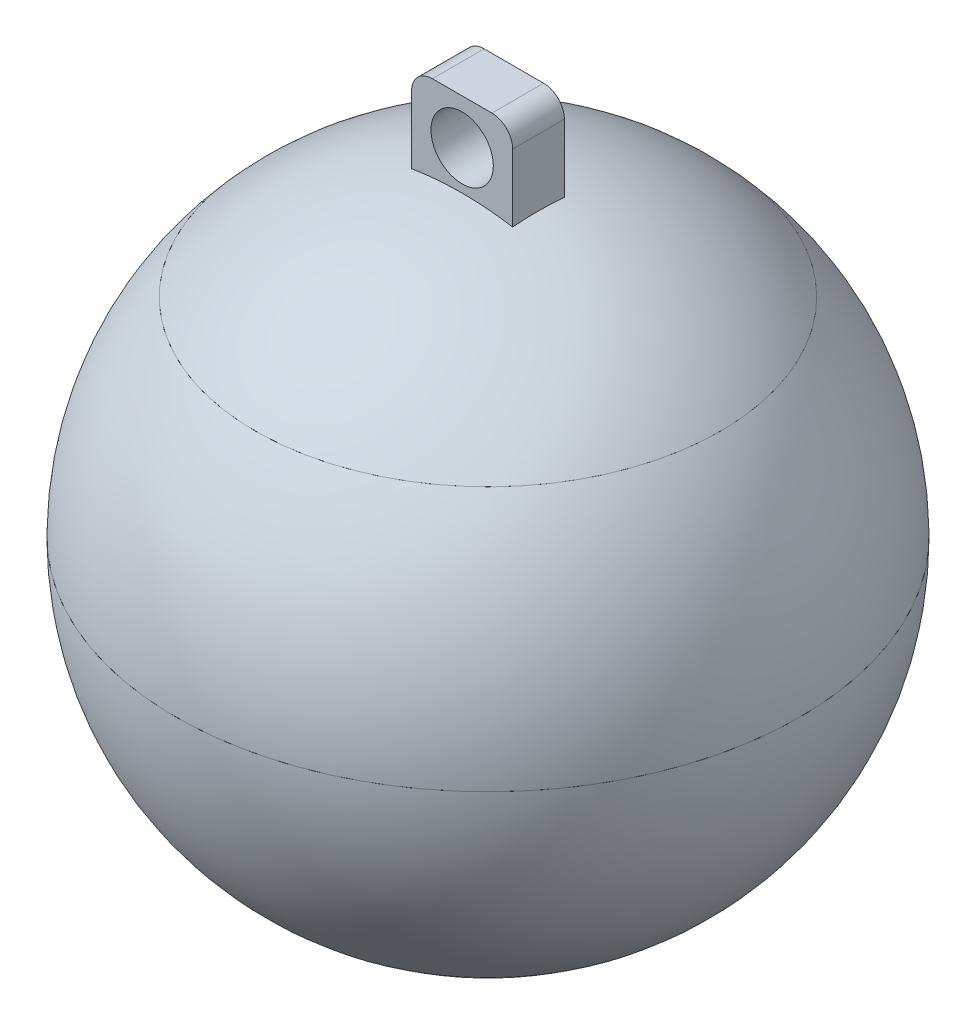
SolidWorks part; units mm, degrees
ref_plane "Front Plane" through (0, 0, 0) normal (0, 0, 1) x (1, 0, 0)
ref_plane "Top Plane" through (0, 0, 0) normal (0, 1, 0) x (1, 0, 0)
ref_plane "Right Plane" through (0, 0, 0) normal (1, 0, 0) x (0, 0, -1)
sketch "Sketch1" plane through (0, 0, 0) normal (0, 0, 1) x (1, 0, 0)
  line L0 (0, 0) -> (0, -15)
  line L1 (0, 0) -> (-15, 0)
  arc A0 (-15, 0) -> (0, -15) centre (0, 0) ccw
revolve "Revolve1" add sketch "Sketch1" angle 360 about L0
sketch "Sketch3" plane through (0, 0, 0) normal (0, 0, 1) x (1, 0, 0)
  line L0 (-15, 0) -> (0, 0)
  line L1 (0, 0) -> (0, 10)
  line L2 (0, 0) -> (0, 10) construction
  line L3 (0, 10) -> (-11.1803, 10)
  arc A0 (-11.1803, 10) -> (-15, 0) centre (0, 0) ccw
revolve "Revolve3" add sketch "Sketch3" angle 360 about L2
sketch "Sketch4" plane through (0, 0, 0) normal (0, 0, 1) x (1, 0, 0)
  line L0 (0, 10) -> (0, 15)
  line L1 (0, 10) -> (-11.1803, 10)
  line L2 (11.1803, 10) -> (-11.1803, 10) construction
  arc A0 (0, 15) -> (-11.1803, 10) centre (0, 0) ccw
revolve "Revolve4" add sketch "Sketch4" angle 360 about L0
sketch "Sketch5" plane through (0, 0, 0) normal (0, 1, 0) x (1, 0, 0)
  line L1 (-2.4306, 1.2436) -> (2.4306, 1.2436)
  line L2 (-2.4306, 1.2436) -> (-2.4306, -1.2436)
  line L3 (-2.4306, -1.2436) -> (2.4306, -1.2436)
  line L4 (2.4306, 1.2436) -> (2.4306, -1.2436)
  line L5 (-2.4306, 1.2436) -> (2.4306, -1.2436) construction
  line L6 (-2.4306, -1.2436) -> (2.4306, 1.2436) construction
  point P0 (0, 0)
extrude "Boss-Extrude1" add sketch "Sketch5" against normal blind 5 from offset 19
fillet "Fillet1" radius 1 2 edges at (2.4306, 19, 0) (-2.4306, 19, 0)
sketch "Sketch6" plane through (0, 0, 1.2436) normal (0, 0, 1) x (1, 0, 0)
  circle A0 centre (0, 16.8335) radius 1.5
extrude "Cut-Extrude1" cut sketch "Sketch6" against normal blind 5
